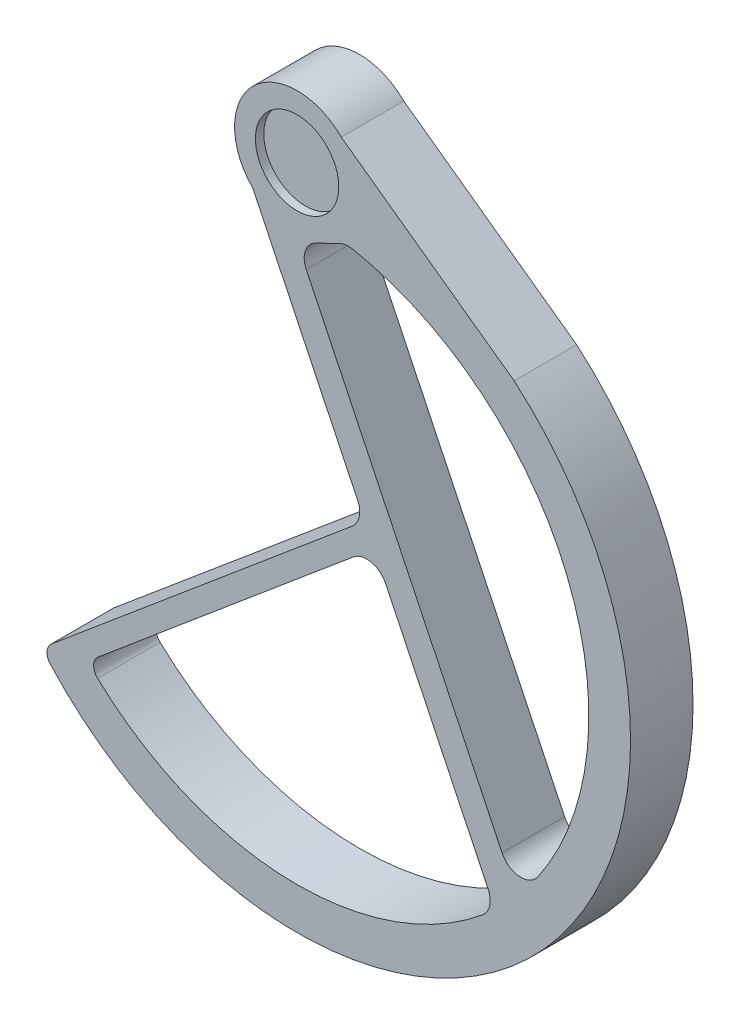
SolidWorks part; units mm, degrees
ref_plane "正面" through (0, 0, 0) normal (0, 0, 1) x (1, 0, 0)
ref_plane "平面" through (0, 0, 0) normal (0, 1, 0) x (1, 0, 0)
ref_plane "右側面" through (0, 0, 0) normal (1, 0, 0) x (0, 0, -1)
sketch "ｽｹｯﾁ4" plane through (0, 0, 0) normal (0, 0, 1) x (1, 0, 0)
  line L0 (0, 0.7897) -> (0, 0)
  line L1 (-53.6231, -124.9951) -> (-58.9406, -129.4571)
  line L3 (-10.6066, -10.6066) -> (14.5363, -62.8896)
  line L4 (-53.6231, -124.9951) -> (13.2442, -68.8868)
  line L5 (21.2324, -76.8138) -> (45.8448, -127.9938)
  line L6 (10.6066, 10.6066) -> (52.0762, -19.2705)
  line L7 (-58.0696, -135.2532) -> (-57.9498, -135.1527)
  line L8 (-47.7477, -126.5866) -> (13.5112, -75.1515)
  arc A1 (-59.2335, -133.7716) -> (52.0762, -19.2705) centre (0, -80) ccw
  arc A2 (-47.8702, -131.073) -> (44.5187, -134.0193) centre (0, -80) ccw
  arc A3 (10.6066, 10.6066) -> (-10.6066, -10.6066) centre (0, 0) ccw
  arc A4 (-59.2335, -133.7716) -> (-58.9406, -129.4571) centre (-57.0123, -131.7552) cw
  arc A5 (-47.8702, -131.073) -> (-47.7477, -126.5866) centre (-45.8186, -128.8841) cw
  arc A6 (13.5112, -75.1515) -> (21.2324, -76.8138) centre (16.7264, -78.9807) cw
  arc A7 (13.2442, -68.8868) -> (14.5363, -62.8896) centre (10.0302, -65.0566) ccw
  arc A8 (45.8448, -127.9938) -> (44.5187, -134.0193) centre (41.3388, -130.1608) cw
  point P18 (-61.2836, -131.423)
  point P21 (-50.2744, -128.7081)
  point P24 (18.4421, -71.0114)
  dimension "D3" = 140
  dimension "D4" = 30
  dimension "D5" = 5
  dimension "D6" = 3
  dimension "D7" = 3
  dimension "D8" = 5
  dimension "D9" = 5
  dimension "D10" = 5
  dimension "D2" = 5
extrude "ﾎﾞｽ - 押し出し1" add sketch "ｽｹｯﾁ4" along normal blind 15
sketch "ｽｹｯﾁ6" plane through (0, 0, 15) normal (0, 0, 1) x (1, 0, 0)
  line L6 (49.1896, -118.7973) -> (2.2018, -21.089)
  line L7 (6.4834, -13.4819) -> (4.5408, -14.416)
  line L8 (6.4834, -13.4819) -> (10.2197, -11.6851)
  arc A0 (57.8261, -119.448) -> (13.3394, -11.2828) centre (0, -80) ccw
  arc A1 (2.2018, -21.089) -> (4.5408, -14.416) centre (6.7078, -18.9221) cw
  arc A2 (13.3394, -11.2828) -> (10.2197, -11.6851) centre (12.3866, -16.1911) ccw
  arc A3 (57.8261, -119.448) -> (49.1896, -118.7973) centre (53.6956, -116.6303) cw
  point P7 (0.0348, -16.583)
  point P14 (52.6925, -126.0814)
  dimension "D3" = 121.502
  dimension "D4" = 70
  dimension "D1" = 5
  dimension "D2" = 5
  dimension "D5" = 5
  dimension "D6" = 90
extrude "ｶｯﾄ - 押し出し1" cut sketch "ｽｹｯﾁ6" against normal blind 15
sketch "ｽｹｯﾁ7" plane through (0, 0, 15) normal (0, 0, 1) x (1, 0, 0)
  circle A0 centre (0, 0) radius 10
extrude "ｶｯﾄ - 押し出し2" cut sketch "ｽｹｯﾁ7" against normal blind 2
